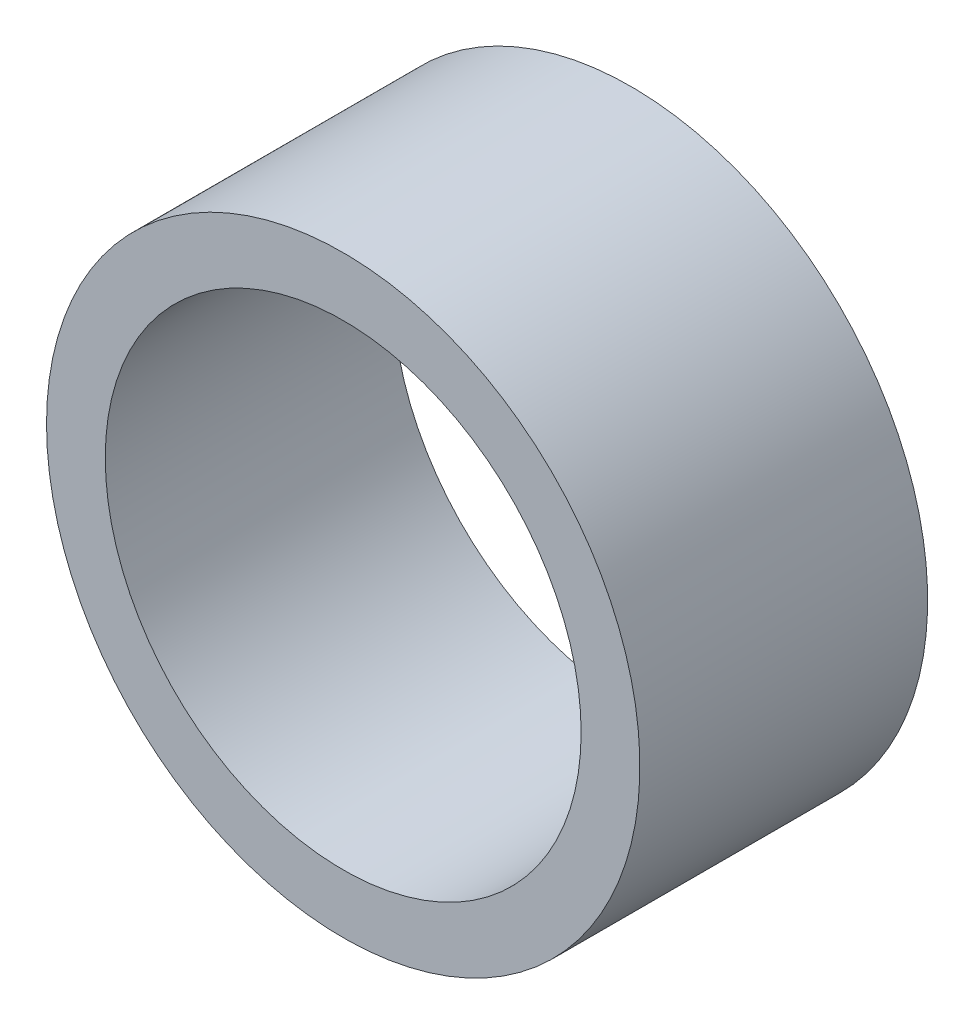
SolidWorks part; units mm, degrees
ref_plane "正面" through (0, 0, 0) normal (0, 0, 1) x (1, 0, 0)
ref_plane "平面" through (0, 0, 0) normal (0, 1, 0) x (1, 0, 0)
ref_plane "右側面" through (0, 0, 0) normal (1, 0, 0) x (0, 0, -1)
sketch "ｽｹｯﾁ1" plane through (0, 0, 0) normal (0, 0, 1) x (1, 0, 0)
  circle A0 centre (0, 0) radius 25
  circle A1 centre (0, 0) radius 20.05
extrude "ﾎﾞｽ - 押し出し1" add sketch "ｽｹｯﾁ1" along normal blind 24.25
